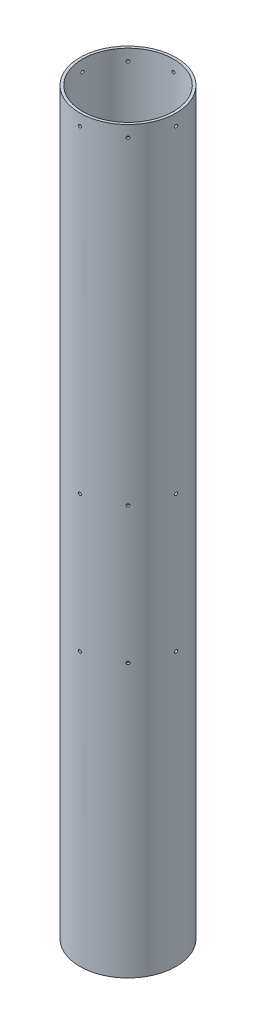
SolidWorks part; units mm, degrees
material "Hexcel AS4C (3000 Filaments)"
ref_plane "Front Plane" through (0, 0, 0) normal (0, 0, 1) x (1, 0, 0)
ref_plane "Top Plane" through (0, 0, 0) normal (0, 1, 0) x (1, 0, 0)
ref_plane "Right Plane" through (0, 0, 0) normal (1, 0, 0) x (0, 0, -1)
sketch "Sketch1" plane through (0, 0, 0) normal (0, 1, 0) x (1, 0, 0)
  circle A0 centre (0, 0) radius 50.8
  dimension "D1" = 101.6
extrude "Tube Extrusion" add sketch "Sketch1" along normal blind 825.5 thin
ref_plane "Hole Plane" through (0, 0, 53.721) normal (0, 0, 1) x (1, 0, 0)
sketch "Sketch3" plane through (0, 0, 53.721) normal (0, 0, 1) x (1, 0, 0)
  line L0 (0, 825.5) -> (0, 0) construction
  line L1 (50.8, 825.5) -> (-50.8, 825.5) construction
  line L2 (53.721, 825.5) -> (-53.721, 825.5) construction
  circle A0 centre (0, 457.2) radius 1.6383
  circle A1 centre (0, 304.8) radius 1.6383
  circle A2 centre (0, 812.8) radius 1.6383
  dimension "D1" = 3.2766
  dimension "D3" = 3.2766
  dimension "D5" = 3.2766
  dimension "D2" = 368.3
  dimension "D4" = 520.7
  dimension "D6" = 12.7
extrude "Bulkhead Holes" cut sketch "Sketch3" against normal up to next
pattern_circular "CirPattern1" count 8 over 360 about axis through (0, 825.5, 0) along (0, -1, 0) of "Bulkhead Holes"
